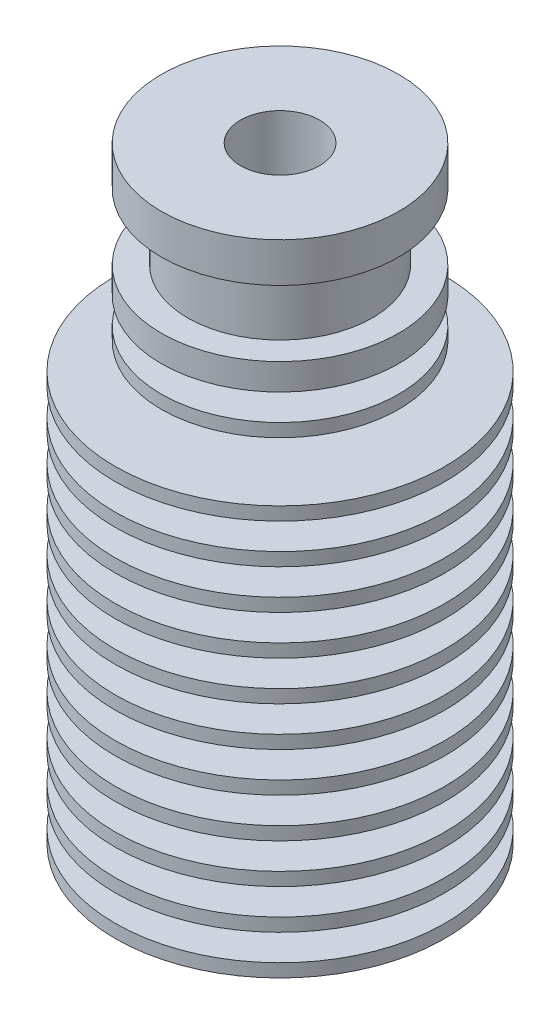
SolidWorks part; units mm, degrees
ref_plane "前视基准面" through (0, 0, 0) normal (0, 0, 1) x (1, 0, 0)
ref_plane "上视基准面" through (0, 0, 0) normal (0, 1, 0) x (1, 0, 0)
ref_plane "右视基准面" through (0, 0, 0) normal (1, 0, 0) x (0, 0, -1)
sketch "草图1" plane through (0, 0, 0) normal (0, 1, 0) x (1, 0, 0)
  circle A1 centre (0, 0) radius 12.5
extrude "凸台-拉伸1" add sketch "草图1" along normal blind 1
sketch "草图5" plane through (0, 1, 0) normal (0, 1, 0) x (1, 0, 0)
  circle A0 centre (0, 0) radius 4
extrude "凸台-拉伸4" add sketch "草图5" along normal blind 2
sketch "草图6" plane through (0, 3, 0) normal (0, 1, 0) x (1, 0, 0)
  circle A0 centre (0, 0) radius 12.5
extrude "凸台-拉伸5" add sketch "草图6" along normal blind 1
sketch "草图7" plane through (0, 4, 0) normal (0, 1, 0) x (1, 0, 0)
  circle A0 centre (0, 0) radius 4
extrude "凸台-拉伸6" add sketch "草图7" along normal blind 2
sketch "草图8" plane through (0, 6, 0) normal (0, 1, 0) x (1, 0, 0)
  circle A0 centre (0, 0) radius 12.5
extrude "凸台-拉伸7" add sketch "草图8" along normal blind 1
sketch "草图9" plane through (0, 7, 0) normal (0, 1, 0) x (1, 0, 0)
  circle A0 centre (0, 0) radius 4
extrude "凸台-拉伸8" add sketch "草图9" along normal blind 2
sketch "草图10" plane through (0, 9, 0) normal (0, 1, 0) x (1, 0, 0)
  circle A0 centre (0, 0) radius 12.5
extrude "凸台-拉伸9" add sketch "草图10" along normal blind 1
sketch "草图11" plane through (0, 10, 0) normal (0, 1, 0) x (1, 0, 0)
  circle A0 centre (0, 0) radius 4
extrude "凸台-拉伸10" add sketch "草图11" along normal blind 2
sketch "草图12" plane through (0, 12, 0) normal (0, 1, 0) x (1, 0, 0)
  circle A0 centre (0, 0) radius 12.5
extrude "凸台-拉伸11" add sketch "草图12" along normal blind 1
sketch "草图13" plane through (0, 13, 0) normal (0, 1, 0) x (1, 0, 0)
  circle A0 centre (0, 0) radius 4
extrude "凸台-拉伸12" add sketch "草图13" along normal blind 2
sketch "草图14" plane through (0, 15, 0) normal (0, 1, 0) x (1, 0, 0)
  circle A0 centre (0, 0) radius 12.5
extrude "凸台-拉伸13" add sketch "草图14" along normal blind 1
sketch "草图15" plane through (0, 16, 0) normal (0, 1, 0) x (1, 0, 0)
  circle A0 centre (0, 0) radius 4
extrude "凸台-拉伸14" add sketch "草图15" along normal blind 2
sketch "草图16" plane through (0, 18, 0) normal (0, 1, 0) x (1, 0, 0)
  circle A0 centre (0, 0) radius 12.5
extrude "凸台-拉伸15" add sketch "草图16" along normal blind 1
sketch "草图17" plane through (0, 19, 0) normal (0, 1, 0) x (1, 0, 0)
  circle A0 centre (0, 0) radius 4
extrude "凸台-拉伸16" add sketch "草图17" along normal blind 2
sketch "草图18" plane through (0, 21, 0) normal (0, 1, 0) x (1, 0, 0)
  circle A0 centre (0, 0) radius 12.5
extrude "凸台-拉伸17" add sketch "草图18" along normal blind 1
sketch "草图19" plane through (0, 22, 0) normal (0, 1, 0) x (1, 0, 0)
  circle A0 centre (0, 0) radius 4
extrude "凸台-拉伸18" add sketch "草图19" along normal blind 2
sketch "草图20" plane through (0, 24, 0) normal (0, 1, 0) x (1, 0, 0)
  circle A0 centre (0, 0) radius 12.5
extrude "凸台-拉伸19" add sketch "草图20" along normal blind 1
sketch "草图21" plane through (0, 25, 0) normal (0, 1, 0) x (1, 0, 0)
  circle A0 centre (0, 0) radius 4
extrude "凸台-拉伸20" add sketch "草图21" along normal blind 2
sketch "草图22" plane through (0, 27, 0) normal (0, 1, 0) x (1, 0, 0)
  circle A0 centre (0, 0) radius 12.5
extrude "凸台-拉伸21" add sketch "草图22" along normal blind 1
sketch "草图23" plane through (0, 28, 0) normal (0, 1, 0) x (1, 0, 0)
  circle A0 centre (0, 0) radius 4
extrude "凸台-拉伸22" add sketch "草图23" along normal blind 2
sketch "草图24" plane through (0, 30, 0) normal (0, 1, 0) x (1, 0, 0)
  circle A0 centre (0, 0) radius 12.5
extrude "凸台-拉伸23" add sketch "草图24" along normal blind 1
sketch "草图25" plane through (0, 31, 0) normal (0, 1, 0) x (1, 0, 0)
  circle A0 centre (0, 0) radius 4
extrude "凸台-拉伸24" add sketch "草图25" along normal blind 2
sketch "草图26" plane through (0, 33, 0) normal (0, 1, 0) x (1, 0, 0)
  circle A0 centre (0, 0) radius 9
extrude "凸台-拉伸25" add sketch "草图26" along normal blind 1
sketch "草图27" plane through (0, 34, 0) normal (0, 1, 0) x (1, 0, 0)
  circle A0 centre (0, 0) radius 4
extrude "凸台-拉伸26" add sketch "草图27" along normal blind 2
sketch "草图28" plane through (0, 36, 0) normal (0, 1, 0) x (1, 0, 0)
  circle A0 centre (0, 0) radius 9
extrude "凸台-拉伸27" add sketch "草图28" along normal blind 2
sketch "草图29" plane through (0, 38, 0) normal (0, 1, 0) x (1, 0, 0)
  circle A0 centre (0, 0) radius 7
extrude "凸台-拉伸28" add sketch "草图29" along normal blind 5
sketch "草图30" plane through (0, 43, 0) normal (0, 1, 0) x (1, 0, 0)
  circle A0 centre (0, 0) radius 9
extrude "凸台-拉伸29" add sketch "草图30" along normal blind 3
sketch "草图31" plane through (0, 0, 0) normal (0, -1, 0) x (-1, 0, 0)
  circle A0 centre (0, 0) radius 3
extrude "切除-拉伸1" cut sketch "草图31" against normal through all
